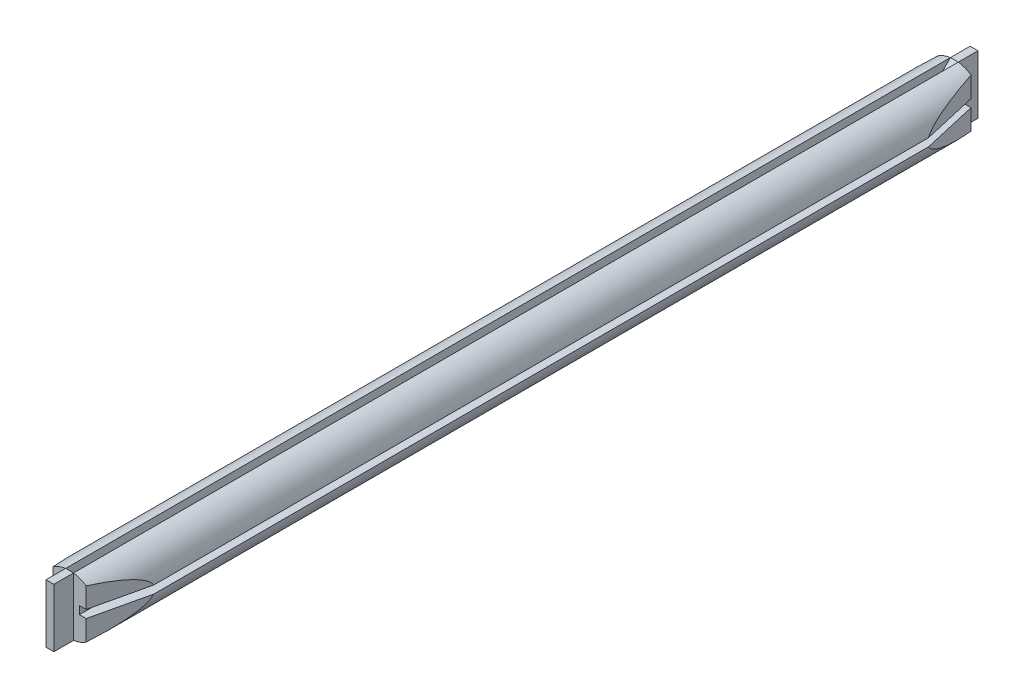
SolidWorks part; units mm, degrees
ref_plane "Front Plane" through (0, 0, 0) normal (0, 0, 1) x (1, 0, 0)
ref_plane "Top Plane" through (0, 0, 0) normal (0, 1, 0) x (1, 0, 0)
ref_plane "Right Plane" through (0, 0, 0) normal (1, 0, 0) x (0, 0, -1)
sketch "Sketch1" plane through (0, 0, 0) normal (0, 0, 1) x (1, 0, 0)
  line L0 (3.3454, 176.2824) -> (3.3454, 56.4598) construction
  line L1 (-6.6546, 55.7901) -> (-6.6546, 6.4598)
  line L2 (-6.6546, 6.4598) -> (13.3454, 6.4598)
  line L3 (13.3454, 55.7901) -> (13.3454, 6.4598)
  line L4 (-25.8595, -18.5402) -> (28.5608, -18.5402) construction
  line L5 (77.6757, -28.5402) -> (28.3454, -28.5402)
  line L6 (77.6757, -8.5402) -> (28.3454, -8.5402)
  line L7 (28.3454, -8.5402) -> (28.3454, -28.5402)
  line L8 (-6.6546, -92.8705) -> (-6.6546, -43.5402)
  line L9 (13.3454, -92.8705) -> (13.3454, -43.5402)
  line L10 (13.3454, -43.5402) -> (-6.6546, -43.5402)
  line L11 (-70.985, -8.5402) -> (-21.6546, -8.5402)
  line L12 (-70.985, -28.5402) -> (-21.6546, -28.5402)
  line L13 (-21.6546, -28.5402) -> (-21.6546, -8.5402)
  line L14 (3.3454, 56.4598) -> (3.3454, 6.4598) construction
  line L15 (3.3454, 6.4598) -> (3.3454, -262.3603) construction
  arc A1 (-6.6546, 55.7901) -> (-70.985, -8.5402) centre (3.3454, -18.5402) ccw
  arc A2 (-70.985, -28.5402) -> (-6.6546, -92.8705) centre (3.3454, -18.5402) ccw
  arc A3 (13.3454, -92.8705) -> (77.6757, -28.5402) centre (3.3454, -18.5402) ccw
  arc A4 (77.6757, -8.5402) -> (13.3454, 55.7901) centre (3.3454, -18.5402) ccw
  arc A5 (13.3454, 55.7901) -> (32.6342, 50.5044) centre (3.3454, -18.5402) cw
  point P1 (3.3454, 6.4598)
  point P4 (3.3454, 75.2096)
  point P23 (-96.6546, -18.5402)
  point P28 (3.3454, -18.5402)
  point P29 (3.3454, -18.5402)
  dimension "D1" = 20
  dimension "D2" = 150
  dimension "D3" = 50
extrude "Boss-Extrude1" add sketch "Sketch1" along normal blind 1125 contours L6 A4 L3 L2 L1 A1 L11 L13 L12 A2 L8 L10 L9 A3 L5 L7
sketch "Sketch2" plane through (0, 0, 0) normal (0, 1, 0) x (1, 0, 0)
  line L3 (-70.985, -1125) -> (-70.985, 0) construction
  line L4 (-70.985, -140) -> (-38.8198, 0)
  line L5 (-6.6546, 0) -> (-70.985, 0) construction
  line L7 (-70.985, -140) -> (-70.985, 0)
  line L9 (-70.985, 0) -> (-38.8198, 0)
  line L10 (3.3454, 0) -> (3.3454, -140) construction
  line L12 (77.6757, 0) -> (45.5105, 0)
  line L13 (77.6757, -140) -> (77.6757, 0)
  line L14 (77.6757, -140) -> (45.5105, 0)
extrude "Cut-Extrude1" cut sketch "Sketch2" against normal mid plane 220
sketch "Sketch3" plane through (-6.6546, 0, 0) normal (1, 0, 0) x (0, 0, -1)
  line L0 (0, 55.7901) -> (0, -92.8705)
  line L1 (0, -92.8705) -> (-74.3303, -18.5402)
  line L2 (-74.3303, -18.5402) -> (0, 55.7901)
extrude "Boss-Extrude2" add sketch "Sketch3" along normal up to surface (20 mm away) up to face at (13.3454, 31.125, 562.5)
sketch "Sketch4" plane through (0, 0, 0) normal (0, 0, -1) x (-1, 0, 0)
  line L0 (-28.3454, -18.5402) -> (21.6546, -18.5402)
  line L1 (-28.3454, -8.5402) -> (-28.3454, -28.5402) construction
  line L2 (21.6546, -28.5402) -> (21.6546, -8.5402) construction
  line L4 (-13.3454, 55.7901) -> (6.6546, 55.7901)
  line L5 (-13.3454, 55.7901) -> (-13.3454, -92.8705)
  line L6 (-13.3454, -92.8705) -> (6.6546, -92.8705)
  line L7 (6.6546, 55.7901) -> (6.6546, -92.8705)
  line L8 (-13.3454, 55.7901) -> (6.6546, -92.8705) construction
  line L9 (-13.3454, -92.8705) -> (6.6546, 55.7901) construction
  arc A0 (6.6546, -92.8705) -> (38.8198, -80.5652) centre (-3.3454, -18.5402) ccw construction
  point P6 (-3.3454, -18.5402)
  line M2 (-13.3454, -92.8705) -> (6.6546, -92.8705)
  line M10 (6.6546, 55.7901) -> (-13.3454, 55.7901)
extrude "Boss-Extrude3" add sketch "Sketch4" along normal blind 50 contours L7 L0 L5 M2 | L7 L5 L0 M10
ref_plane "Plane1" through (3.3454, 0, 0) normal (-1, 0, 0) x (0, 0, 1)
mirror "Mirror1" about plane through (0, 0, 1125) normal (0, 0, 1) of "Boss-Extrude1", "Cut-Extrude1", "Boss-Extrude2", "Boss-Extrude3"
